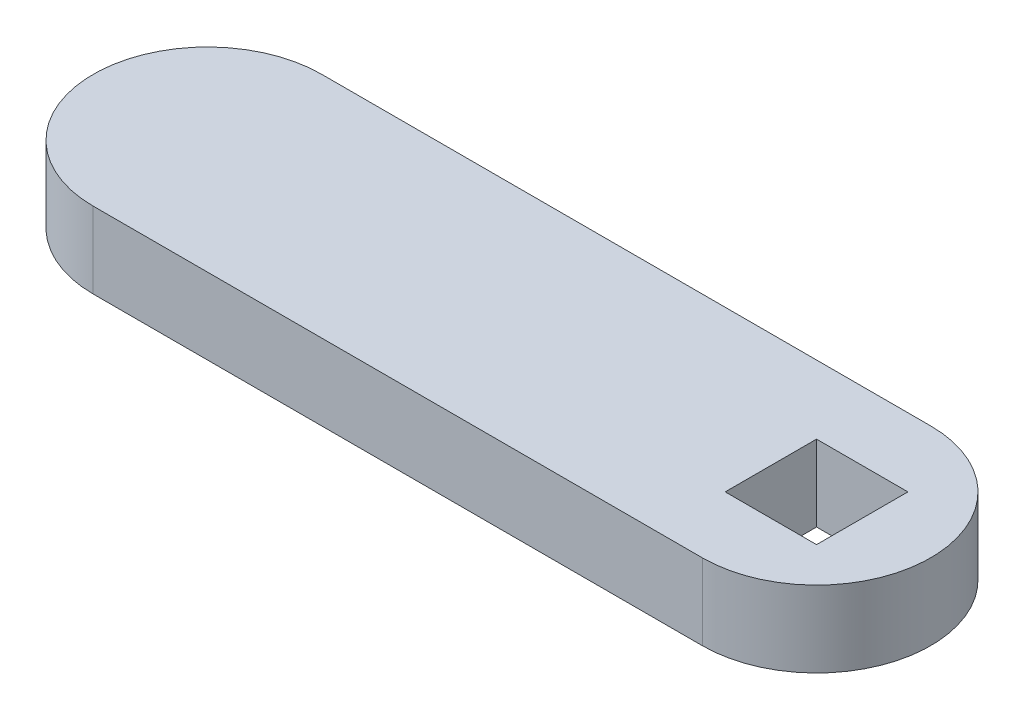
SolidWorks part; units mm, degrees
ref_plane "前视基准面" through (0, 0, 0) normal (0, 0, 1) x (1, 0, 0)
ref_plane "上视基准面" through (0, 0, 0) normal (0, 1, 0) x (1, 0, 0)
ref_plane "右视基准面" through (0, 0, 0) normal (1, 0, 0) x (0, 0, -1)
other "Configuration Table"
sketch "草图1" plane through (0, 0, 0) normal (0, 1, 0) x (1, 0, 0)
  line L0 (0, 0) -> (400, 0) construction
  line L1 (0, 75) -> (400, 75)
  line L2 (0, -75) -> (400, -75)
  line L4 (370, 30) -> (430, 30)
  line L5 (370, 30) -> (370, -30)
  line L6 (370, -30) -> (430, -30)
  line L7 (430, 30) -> (430, -30)
  line L8 (370, 30) -> (430, -30) construction
  line L9 (370, -30) -> (430, 30) construction
  arc A0 (0, 75) -> (0, -75) centre (0, 0) ccw
  arc A1 (400, -75) -> (400, 75) centre (400, 0) ccw
  point P3 (200, 0)
  point P8 (400, 0)
  dimension "D2" = 75
  dimension "D1" = 400
  dimension "D3" = 60
  dimension "D4" = 60
extrude "凸台-拉伸1" add sketch "草图1" along normal blind 50
